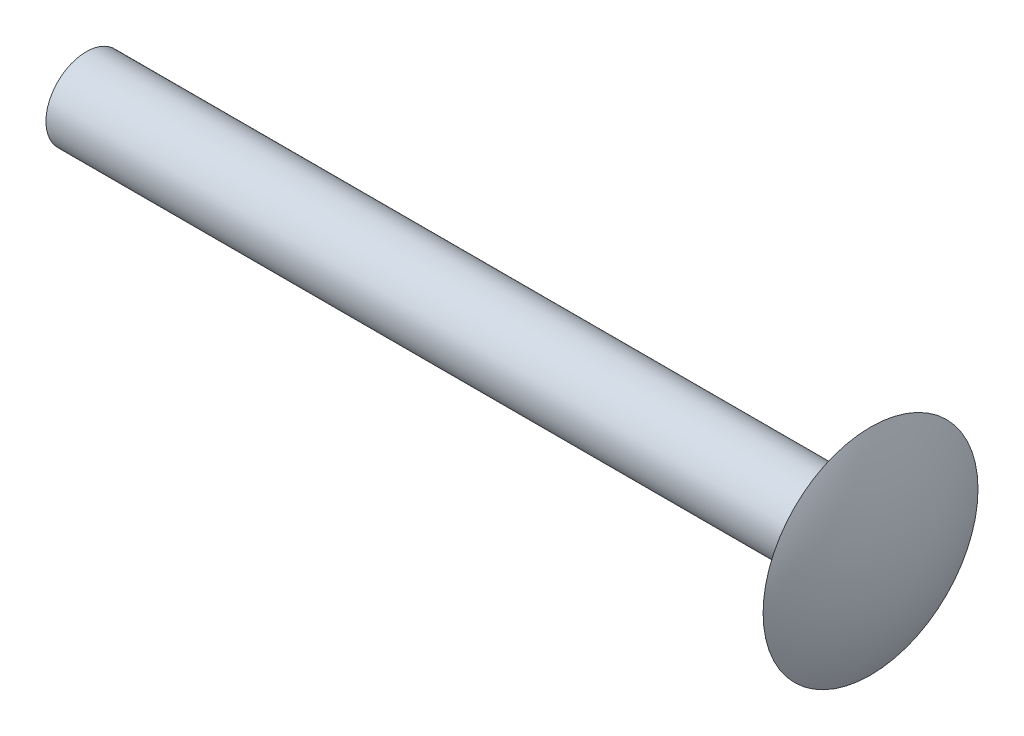
SolidWorks part; units mm, degrees
ref_plane "Front Plane" through (0, 0, 0) normal (0, 0, 1) x (1, 0, 0)
ref_plane "Top Plane" through (0, 0, 0) normal (0, 1, 0) x (1, 0, 0)
ref_plane "Right Plane" through (0, 0, 0) normal (1, 0, 0) x (0, 0, -1)
sketch "Shaft Sketch" plane through (0, 0, 0) normal (1, 0, 0) x (0, 0, -1)
  circle A0 centre (0, 0) radius 7.5
  dimension "D1" = 15
extrude "Shaft Extrude" add sketch "Shaft Sketch" along normal blind 146
sketch "Head Sketch" plane through (0, 0, 0) normal (0, 0, 1) x (1, 0, 0)
  line L0 (151, 0) -> (146, 0)
  line L1 (146, 0) -> (146, 20)
  line L2 (146, -7.5) -> (146, 7.5) construction
  arc A0 (151, 0) -> (146, 20) centre (108.5, 0) ccw
  dimension "D1" = 20
  dimension "D2" = 5
revolve "Head Revolution" add sketch "Head Sketch" angle 360 about L0
